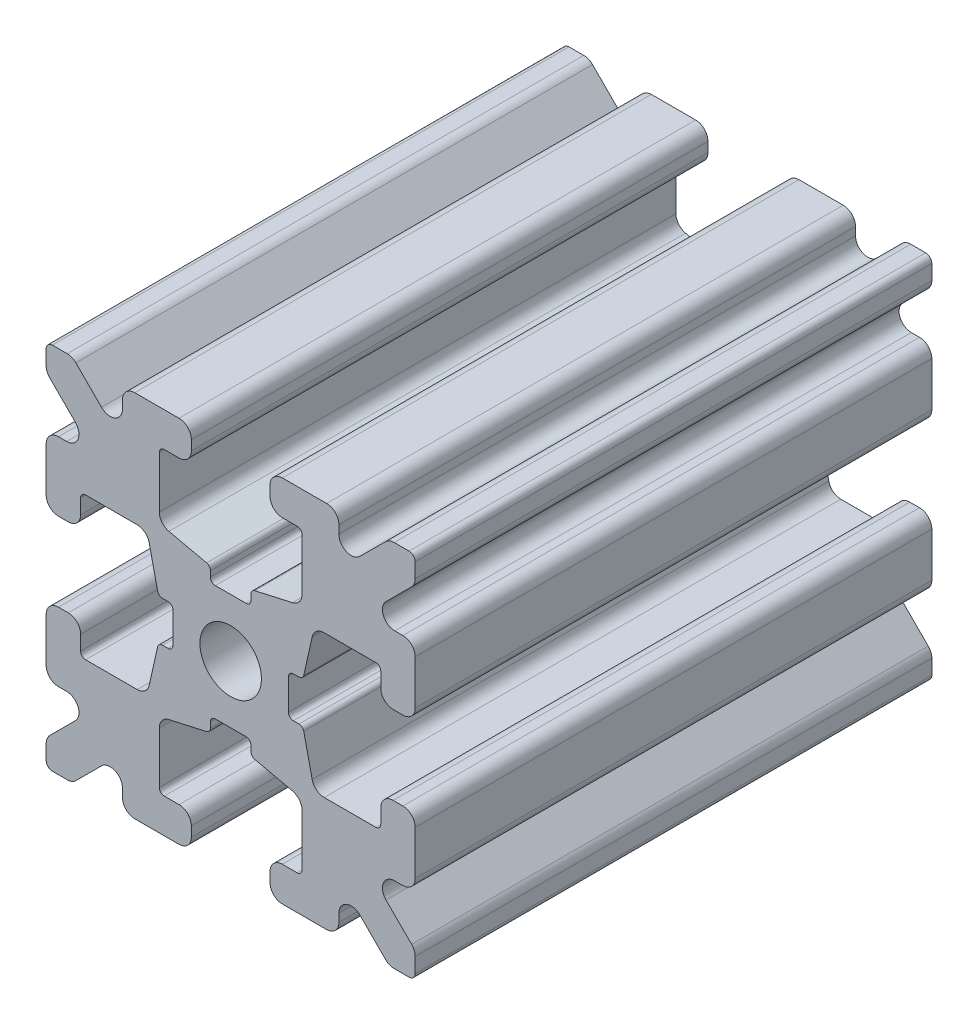
SolidWorks part; units mm, degrees
ref_plane "Front Plane" through (0, 0, 0) normal (0, 0, 1) x (1, 0, 0)
ref_plane "Top Plane" through (0, 0, 0) normal (0, 1, 0) x (1, 0, 0)
ref_plane "Right Plane" through (0, 0, 0) normal (1, 0, 0) x (0, 0, -1)
sketch "Sketch1" plane through (0, 0, 0) normal (0, 0, 1) x (1, 0, 0)
  line L1 (-7.5, -7.5) -> (7.5, -7.5)
  line L2 (-7.5, -7.5) -> (-7.5, 7.5)
  line L3 (-7.5, 7.5) -> (7.5, 7.5)
  line L4 (7.5, -7.5) -> (7.5, 7.5)
  line L5 (-7.5, -7.5) -> (7.5, 7.5) construction
  line L6 (-7.5, 7.5) -> (7.5, -7.5) construction
  circle A0 centre (0, 0) radius 1.25
  point P0 (0, 0)
  dimension "D2" = 2.5
  dimension "D1" = 15
extrude "Boss-Extrude1" add sketch "Sketch1" along normal mid plane 21
fillet "Fillet1" radius 0.25 4 edges at (7.5, -7.5, 0) (-7.5, -7.5, 0) (7.5, 7.5, 0) (-7.5, 7.5, 0)
sketch "Sketch2" plane through (0, 0, 10.5) normal (0, 0, 1) x (1, 0, 0)
  line L0 (-7.5, 7.25) -> (-7.5, -7.25) construction
  line L1 (-7.5, 1.6) -> (-6.1, 1.6)
  line L2 (-7.5, 1.6) -> (-7.5, -1.6)
  line L3 (-7.5, -1.6) -> (-6.1, -1.6)
  line L4 (-6.1, 1.6) -> (-6.1, 2.9)
  line L5 (0, 0) -> (-12.1036, 0) construction
  line L6 (-6.1, -2.9) -> (-3.4, -2.9)
  line L7 (0, 0) -> (-7.25, 7.25) construction
  line L8 (-6.1, 2.9) -> (-3.4, 2.9)
  line L9 (-3.4, -2.9) -> (-3.4, 2.9)
  line L10 (55, 0) -> (-55, 0) construction
  line L11 (-6.1, -2.9) -> (-6.1, -1.6)
  line L12 (2.9, 6.1) -> (1.6, 6.1)
  line L13 (2.9, 3.4) -> (-2.9, 3.4)
  line L14 (-2.9, 6.1) -> (-2.9, 3.4)
  line L15 (2.9, 6.1) -> (2.9, 3.4)
  line L16 (-1.6, 6.1) -> (-2.9, 6.1)
  line L17 (1.6, 7.5) -> (1.6, 6.1)
  line L18 (-1.6, 7.5) -> (1.6, 7.5)
  line L19 (-1.6, 7.5) -> (-1.6, 6.1)
  line L20 (-1.6, -7.5) -> (-1.6, -6.1)
  line L21 (-1.6, -7.5) -> (1.6, -7.5)
  line L22 (1.6, -7.5) -> (1.6, -6.1)
  line L23 (-1.6, -6.1) -> (-2.9, -6.1)
  line L24 (2.9, -6.1) -> (2.9, -3.4)
  line L25 (-2.9, -6.1) -> (-2.9, -3.4)
  line L26 (2.9, -3.4) -> (-2.9, -3.4)
  line L27 (2.9, -6.1) -> (1.6, -6.1)
  line L28 (6.1, -2.9) -> (6.1, -1.6)
  line L29 (3.4, -2.9) -> (3.4, 2.9)
  line L30 (6.1, 2.9) -> (3.4, 2.9)
  line L31 (6.1, -2.9) -> (3.4, -2.9)
  line L32 (6.1, 1.6) -> (6.1, 2.9)
  line L33 (7.5, -1.6) -> (6.1, -1.6)
  line L34 (7.5, 1.6) -> (7.5, -1.6)
  line L35 (7.5, 1.6) -> (6.1, 1.6)
  dimension "D1" = 3.2
  dimension "D2" = 5.8
  dimension "D3" = 1.4
  dimension "D4" = 2.7
extrude "Cut-Extrude1" cut sketch "Sketch2" against normal through all
sketch "Sketch4" plane through (0, 0, 10.5) normal (0, 0, 1) x (1, 0, 0)
  line L0 (-3.4, 2.9) -> (-2.75, 0)
  line L1 (55, 0) -> (-55, 0) construction
  line L2 (-2.75, 0) -> (-3.4, -2.9)
  line L3 (-3.4, -2.9) -> (-3.4, 2.9) construction
  line L4 (-3.4, 2.9) -> (-3.4, -2.9)
  line L5 (-2.9, 3.4) -> (0, 2.75)
  line L6 (0, 2.75) -> (2.9, 3.4)
  line L7 (2.9, 3.4) -> (-2.9, 3.4)
  line L8 (3.4, 2.9) -> (2.75, 0)
  line L9 (2.75, 0) -> (3.4, -2.9)
  line L10 (3.4, -2.9) -> (3.4, 2.9)
  line L11 (-2.9, -3.4) -> (0, -2.75)
  line L12 (0, -2.75) -> (2.9, -3.4)
  line L13 (2.9, -3.4) -> (-2.9, -3.4)
  circle A2 centre (0, 0) radius 2.75
  circle A3 centre (0, 0) radius 2.75 construction
  dimension "D1" = 1.5
extrude "Cut-Extrude3" cut sketch "Sketch4" against normal through all
fillet "Fillet3" radius 0.5 16 edges at (-6.1, -1.6, 0) (-7.5, -1.6, 0) (-6.1, 1.6, 0) (-7.5, 1.6, 0) (-1.6, -7.5, 0) (-1.6, -6.1, 0) (1.6, -7.5, 0) (1.6, -6.1, 0) (6.1, -1.6, 0) (7.5, -1.6, 0) (7.5, 1.6, 0) (6.1, 1.6, 0) (1.6, 7.5, 0) (1.6, 6.1, 0) (-1.6, 7.5, 0) (-1.6, 6.1, 0)
fillet "Fillet4" radius 0.5 8 edges at (-3.4, 2.9, 0) (-3.4, -2.9, 0) (2.9, -3.4, 0) (-2.9, -3.4, 0) (3.4, -2.9, 0) (3.4, 2.9, 0) (-2.9, 3.4, 0) (2.9, 3.4, 0)
fillet "Fillet5" radius 3 4 edges at (0, -2.75, 0) (2.75, 0, 0) (-2.75, 0, 0) (0, 2.75, 0)
fillet "Fillet6" radius 0.2 8 edges at (-2.9, -6.1, 0) (2.9, -6.1, 0) (6.1, -2.9, 0) (6.1, 2.9, 0) (2.9, 6.1, 0) (-2.9, 6.1, 0) (-6.1, -2.9, 0) (-6.1, 2.9, 0)
sketch "Sketch5" plane through (0, 0, 10.5) normal (0, 0, 1) x (1, 0, 0)
  line L0 (0, 0) -> (-7.25, 7.25) construction
  line L1 (-7.5, 6.4393) -> (-5.4607, 4.4)
  line L2 (-6.4393, 7.5) -> (-4.4, 5.4607)
  line L3 (-7.5, 4.4) -> (-5.4607, 4.4)
  line L4 (-3.8003, 2.9) -> (-5.9, 2.9) construction
  line L5 (0, 0) -> (-12.1819, 0) construction
  line L6 (-4.4, 7.5) -> (-4.4, 5.4607)
  line L7 (-2.9, 5.9) -> (-2.9, 3.8003) construction
  line L8 (-7.5, 6.4393) -> (-7.5, 4.4)
  line L9 (-7.5, 7.25) -> (-7.5, 2.1) construction
  line L10 (2.1, -7.5) -> (7.25, -7.5) construction
  line L11 (7.5, -7.25) -> (7.5, -2.1) construction
  line L12 (7.25, 7.5) -> (2.1, 7.5) construction
  line L13 (-2.1, 7.5) -> (-7.25, 7.5) construction
  line L14 (-4.4, 7.5) -> (-6.4393, 7.5)
  line L16 (55, 0) -> (-55, 0) construction
  line L17 (0, 0) -> (0, 10.993) construction
  line L18 (0, -54.6431) -> (0, 54.6431) construction
  line L20 (4.4, 7.5) -> (6.4393, 7.5)
  line L22 (7.5, 6.4393) -> (7.5, 4.4)
  line L23 (4.4, 7.5) -> (4.4, 5.4607)
  line L24 (7.5, 4.4) -> (5.4607, 4.4)
  line L25 (6.4393, 7.5) -> (4.4, 5.4607)
  line L26 (7.5, 6.4393) -> (5.4607, 4.4)
  line L27 (7.5, -6.4393) -> (5.4607, -4.4)
  line L28 (6.4393, -7.5) -> (4.4, -5.4607)
  line L29 (7.5, -4.4) -> (5.4607, -4.4)
  line L30 (4.4, -7.5) -> (4.4, -5.4607)
  line L31 (7.5, -6.4393) -> (7.5, -4.4)
  line L33 (4.4, -7.5) -> (6.4393, -7.5)
  line L36 (-4.4, -7.5) -> (-6.4393, -7.5)
  line L38 (-7.5, -6.4393) -> (-7.5, -4.4)
  line L39 (-4.4, -7.5) -> (-4.4, -5.4607)
  line L40 (-7.5, -4.4) -> (-5.4607, -4.4)
  line L41 (-6.4393, -7.5) -> (-4.4, -5.4607)
  line L42 (-7.5, -6.4393) -> (-5.4607, -4.4)
  dimension "D1" = 1.5
  dimension "D2" = 1.5
  dimension "D3" = 1.5
extrude "Cut-Extrude4" cut sketch "Sketch5" against normal through all
fillet "Fillet8" radius 0.5 24 edges at (-5.4607, 4.4, 0) (-7.5, 4.4, 0) (-5.4607, -4.4, 0) (-7.5, -4.4, 0) (-4.4, -7.5, 0) (-4.4, -5.4607, 0) (4.4, -7.5, 0) (4.4, -5.4607, 0) (5.4607, -4.4, 0) (7.5, -4.4, 0) (7.5, 4.4, 0) (5.4607, 4.4, 0) (4.4, 5.4607, 0) (4.4, 7.5, 0) (-4.4, 5.4607, 0) (-4.4, 7.5, 0) (-6.4393, 7.5, 0) (-7.5, 6.4393, 0) (6.4393, 7.5, 0) (7.5, 6.4393, 0) (6.4393, -7.5, 0) (7.5, -6.4393, 0) (-6.4393, -7.5, 0) (-7.5, -6.4393, 0)
sketch "Sketch6" plane through (0, 0, 10.5) normal (0, 0, 1) x (1, 0, 0)
  line L0 (0, 0) -> (0, 11.013) construction
  line L1 (0.6561, 2.8971) -> (2.1235, 2.8971) construction
  line L2 (0, -54.6431) -> (0, 54.6431) construction
  line L3 (0, 0) -> (7.25, 7.25) construction
  line L4 (7.5, 0.8255) -> (7.5, -0.8255)
  line L5 (2.3471, 0.8255) -> (7.5, 0.8255)
  line L6 (0, 0) -> (12.4016, 0) construction
  line L7 (0.8255, -7.5) -> (-0.8255, -7.5)
  line L8 (2.3471, -0.8255) -> (2.3471, 0.8255)
  line L9 (0.8255, -2.3471) -> (0.8255, -7.5)
  line L10 (7.5, -0.8255) -> (2.3471, -0.8255)
  line L11 (-7.5, -0.8255) -> (-2.3471, -0.8255)
  line L12 (-2.3471, -0.8255) -> (-2.3471, 0.8255)
  line L13 (-0.8255, -2.3471) -> (0.8255, -2.3471)
  line L14 (-0.8255, 7.5) -> (-0.8255, 2.3471)
  line L15 (-0.8255, 2.3471) -> (0.8255, 2.3471)
  line L16 (-0.8255, -7.5) -> (-0.8255, -2.3471)
  line L17 (0.8255, 2.3471) -> (0.8255, 7.5)
  line L18 (0.8255, 7.5) -> (-0.8255, 7.5)
  line L19 (3.9, 7.5) -> (2.1, 7.5) construction
  line L20 (-2.3471, 0.8255) -> (-7.5, 0.8255)
  line L21 (-7.5, 0.8255) -> (-7.5, -0.8255)
  point P5 (0, -2.5973)
  point P7 (0, 2.5973)
  dimension "D3" = 0.55
  dimension "D1" = 1.651
extrude "Cut-Extrude5" cut sketch "Sketch6" against normal through all
fillet "Fillet10" radius 0.2 16 edges at (-2.935, 0.8255, 0) (-2.935, -0.8255, 0) (2.935, -0.8255, 0) (2.935, 0.8255, 0) (0.8255, 2.935, 0) (-0.8255, 2.935, 0) (-2.3471, 0.8255, 0) (-2.3471, -0.8255, 0) (0.8255, 2.3471, 0) (-0.8255, 2.3471, 0) (2.3471, 0.8255, 0) (2.3471, -0.8255, 0) (0.8255, -2.935, 0) (0.8255, -2.3471, 0) (-0.8255, -2.3471, 0) (-0.8255, -2.935, 0)
